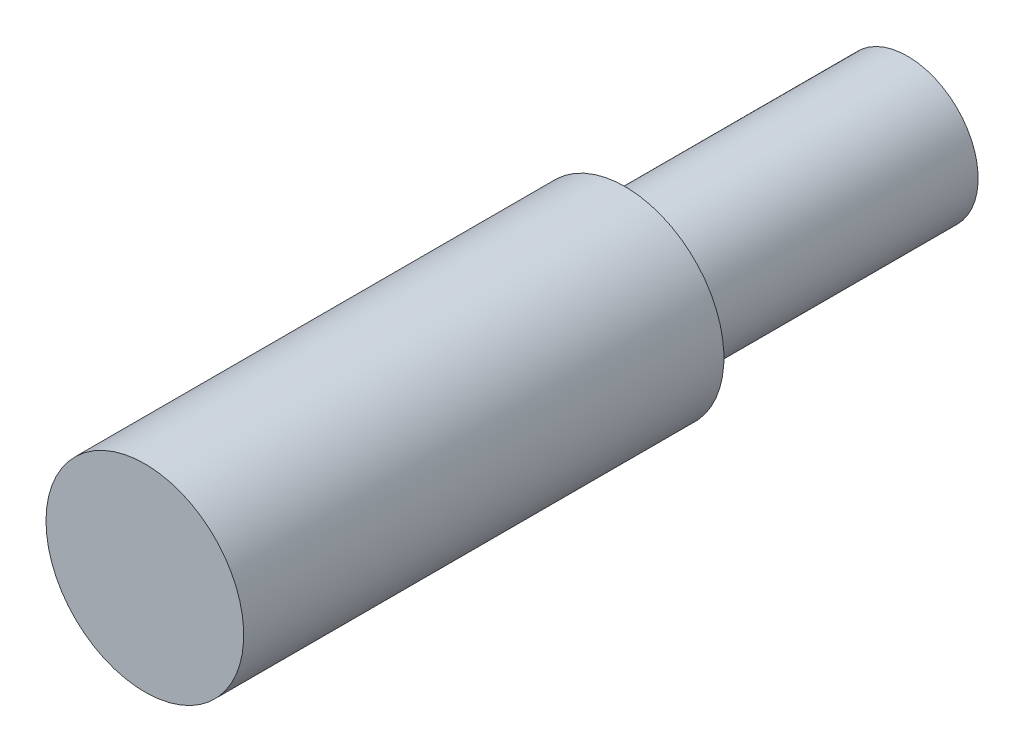
SolidWorks part; units mm, degrees
ref_plane "Front Plane" through (0, 0, 0) normal (0, 0, 1) x (1, 0, 0)
ref_plane "Top Plane" through (0, 0, 0) normal (0, 1, 0) x (1, 0, 0)
ref_plane "Right Plane" through (0, 0, 0) normal (1, 0, 0) x (0, 0, -1)
ref_plane "Plane1" through (0, 0, 108.514) normal (0, 0, 1) x (1, 0, 0)
sketch "Sketch2" plane through (0, 0, 0) normal (0, 0, -1) x (-1, 0, 0)
  circle A0 centre (-15.0578, -8.7614) radius 7
  dimension "D1" = 14
extrude "Boss-Extrude2" add sketch "Sketch2" along normal blind 34
sketch "Sketch3" plane through (0, 0, -34) normal (0, 0, -1) x (-1, 0, 0)
  circle A0 centre (-15.0578, -8.7614) radius 5
  circle A1 centre (-15.0578, -8.7614) radius 7 construction
  point P2 (0, 0)
  dimension "D1" = 10
extrude "Boss-Extrude3" add sketch "Sketch3" along normal blind 20
sketch "Sketch4" plane through (0, 0, -54) normal (0, 0, -1) x (-1, 0, 0)
  circle A0 centre (-15.0578, -8.7614) radius 3
  circle A1 centre (-15.0578, -8.7614) radius 5 construction
  point P2 (0, 0)
  dimension "D1" = 6
extrude "Cut-Extrude1" cut sketch "Sketch4" against normal blind 29
